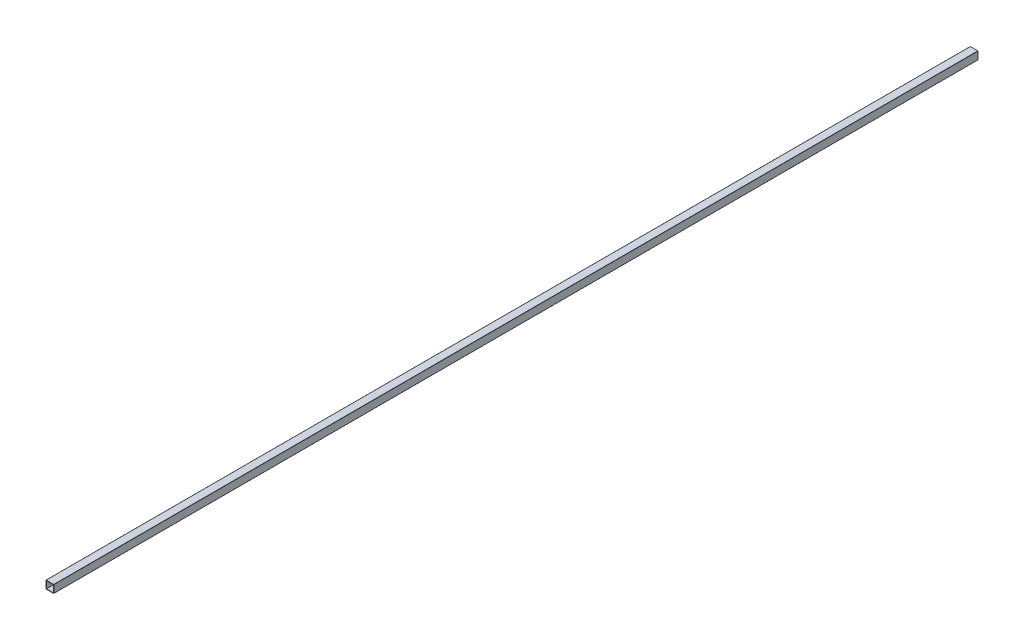
SolidWorks part; units mm, degrees
material "AISI 1035 Acero (SS)"
ref_plane "Alzado" through (0, 0, 0) normal (0, 0, 1) x (1, 0, 0)
ref_plane "Planta" through (0, 0, 0) normal (0, 1, 0) x (1, 0, 0)
ref_plane "Vista lateral" through (0, 0, 0) normal (1, 0, 0) x (0, 0, -1)
sketch "Croquis1" plane through (0, 0, 0) normal (0, 0, 1) x (1, 0, 0)
  line L0 (-22.74, -22.74) -> (-22.74, 22.74)
  line L1 (-24.4, -25.4) -> (24.4, -25.4)
  line L2 (-25.4, -24.4) -> (-25.4, 24.4)
  line L3 (-24.4, 25.4) -> (24.4, 25.4)
  line L4 (25.4, -24.4) -> (25.4, 24.4)
  line L5 (-25.4, -25.4) -> (25.4, 25.4) construction
  line L6 (-25.4, 25.4) -> (25.4, -25.4) construction
  line L7 (-22.74, 22.74) -> (22.74, 22.74)
  line L8 (22.74, -22.74) -> (22.74, 22.74)
  line L9 (-22.74, -22.74) -> (22.74, -22.74)
  line L10 (-25.4, 25.4) -> (25.4, 25.4) construction
  line L11 (25.4, -25.4) -> (25.4, 25.4) construction
  line L12 (-25.4, -25.4) -> (25.4, -25.4) construction
  line L13 (-25.4, -25.4) -> (-25.4, 25.4) construction
  arc A0 (24.4, 25.4) -> (25.4, 24.4) centre (24.4, 24.4) cw
  arc A1 (24.4, -25.4) -> (25.4, -24.4) centre (24.4, -24.4) ccw
  arc A2 (-24.4, -25.4) -> (-25.4, -24.4) centre (-24.4, -24.4) cw
  arc A3 (-25.4, 24.4) -> (-24.4, 25.4) centre (-24.4, 24.4) cw
  point P0 (0, 0)
  dimension "D2" = 1
  dimension "D1" = 50.8
  dimension "D3" = 2.66
extrude "Saliente-Extruir1" add sketch "Croquis1" along normal blind 6000
